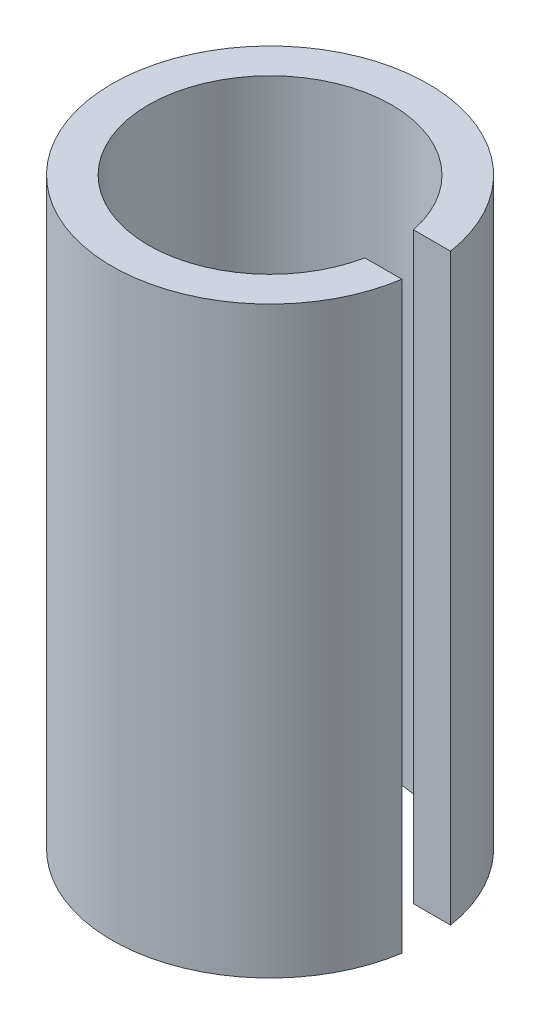
SolidWorks part; units mm, degrees
ref_plane "Front Plane" through (0, 0, 0) normal (0, 0, 1) x (1, 0, 0)
ref_plane "Top Plane" through (0, 0, 0) normal (0, 1, 0) x (1, 0, 0)
ref_plane "Right Plane" through (0, 0, 0) normal (1, 0, 0) x (0, 0, -1)
sketch "Sketch1" plane through (0, 0, 0) normal (0, 1, 0) x (1, 0, 0)
  line L0 (2.4495, 0.5) -> (3.2113, 0.5)
  line L1 (2.4495, -0.5) -> (3.2113, -0.5)
  line L2 (0, 0) -> (3.25, 0) construction
  circle A0 centre (0, 0) radius 3.25
  circle A1 centre (0, 0) radius 2.5
  dimension "D1" = 5
  dimension "D2" = 6.5
  dimension "D3" = 1
  dimension "D4" = 0.5
extrude "Boss-Extrude1" add sketch "Sketch1" along normal blind 12 contours A1 L0 A0 L1
